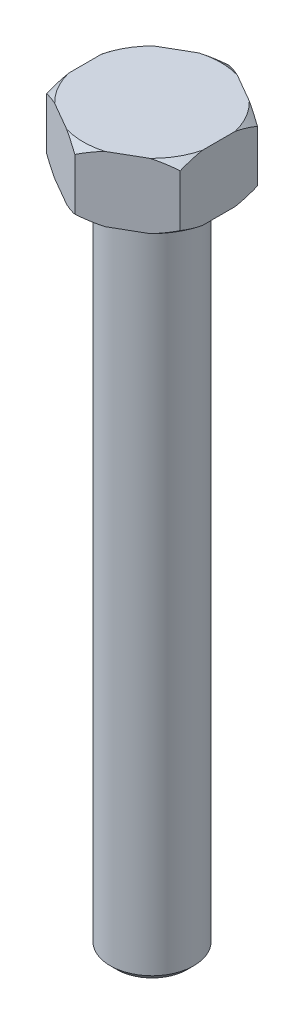
SolidWorks part; units mm, degrees
ref_plane "Front Plane" through (0, 0, 0) normal (0, 0, 1) x (1, 0, 0)
ref_plane "Top Plane" through (0, 0, 0) normal (0, 1, 0) x (1, 0, 0)
ref_plane "Right Plane" through (0, 0, 0) normal (1, 0, 0) x (0, 0, -1)
sketch "Sketch1" plane through (0, 0, 0) normal (0, 1, 0) x (1, 0, 0)
  line L1 (0, -11.7318) -> (10.16, -5.8659)
  line L2 (10.16, -5.8659) -> (10.16, 5.8659)
  line L3 (10.16, 5.8659) -> (0, 11.7318)
  line L4 (0, 11.7318) -> (-10.16, 5.8659)
  line L5 (-10.16, 5.8659) -> (-10.16, -5.8659)
  line L6 (-10.16, -5.8659) -> (0, -11.7318)
  circle A0 centre (0, 0) radius 10.16 construction
  dimension "D1" = 20.32
extrude "Boss-Extrude1" add sketch "Sketch1" along normal blind 9.906
sketch "Sketch3" plane through (0, 0, 0) normal (0, -1, 0) x (1, 0, 0)
  circle A0 centre (0, 0) radius 6.35
  dimension "D1" = 12.7
extrude "Boss-Extrude2" add sketch "Sketch3" along normal blind 101.6
cosmetic thread "Cosmetic Thread1" parameters "D1"=17.78, "D2"=6.2586
chamfer "Chamfer1" distance 0.9906 angle 45 1 edges at (0, -101.6, -6.35)
sketch "Sketch9" plane through (0, 0, 0) normal (1, 0, 0) x (0, 0, -1)
  line L0 (0, 0) -> (0, 12.1671) construction
  line L1 (-11.7318, 9.906) -> (-10.4618, 9.906)
  line L2 (-11.7318, 9.906) -> (-5.8659, 9.906) construction
  line L3 (-10.4618, 9.906) -> (-11.7318, 8.89)
  line L4 (-11.7318, 9.906) -> (-11.7318, 0) construction
  line L5 (-11.7318, 8.89) -> (-11.7318, 9.906)
  line L6 (-11.7318, 0) -> (-10.4618, 0)
  line L7 (-11.7318, 0) -> (-5.8659, 0) construction
  line L8 (-10.4618, 0) -> (-11.7318, 1.016)
  line L9 (-11.7318, 1.016) -> (-11.7318, 0)
  dimension "D1" = 1.016
  dimension "D2" = 1.016
  dimension "D3" = 1.27
  dimension "D4" = 1.27
revolve "Cut-Revolve4" cut sketch "Sketch9" angle 360 about L0
